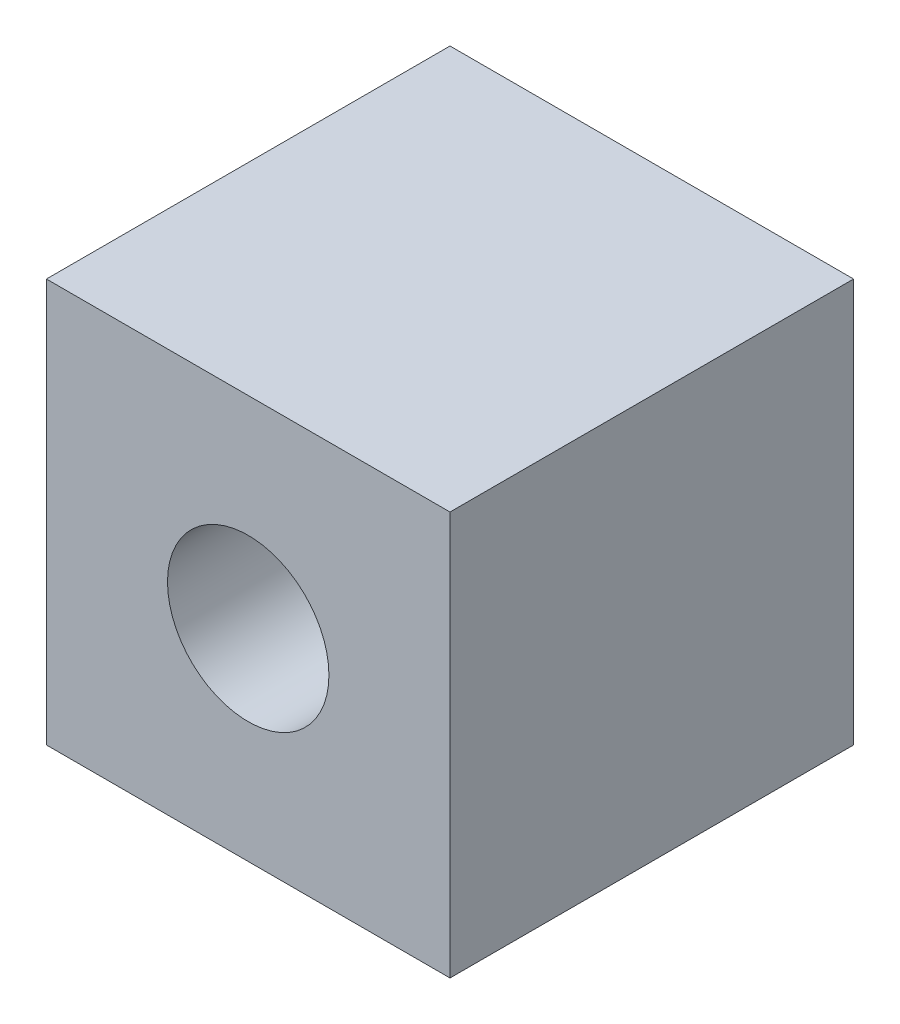
SolidWorks part; units mm, degrees
ref_plane "Front Plane" through (0, 0, 0) normal (0, 0, 1) x (1, 0, 0)
ref_plane "Top Plane" through (0, 0, 0) normal (0, 1, 0) x (1, 0, 0)
ref_plane "Right Plane" through (0, 0, 0) normal (1, 0, 0) x (0, 0, -1)
sketch "Sketch1" plane through (0, 0, 0) normal (0, 0, 1) x (1, 0, 0)
  line L1 (0, 0) -> (10, 0)
  line L2 (0, 0) -> (0, 10)
  line L3 (0, 10) -> (10, 10)
  line L4 (10, 0) -> (10, 10)
extrude "Boss-Extrude1" add sketch "Sketch1" along normal blind 10
sketch "Sketch2" plane through (0, 0, 10) normal (0, 0, 1) x (1, 0, 0)
  circle A0 centre (5, 5) radius 2
extrude "Cut-Extrude1" cut sketch "Sketch2" against normal through all
